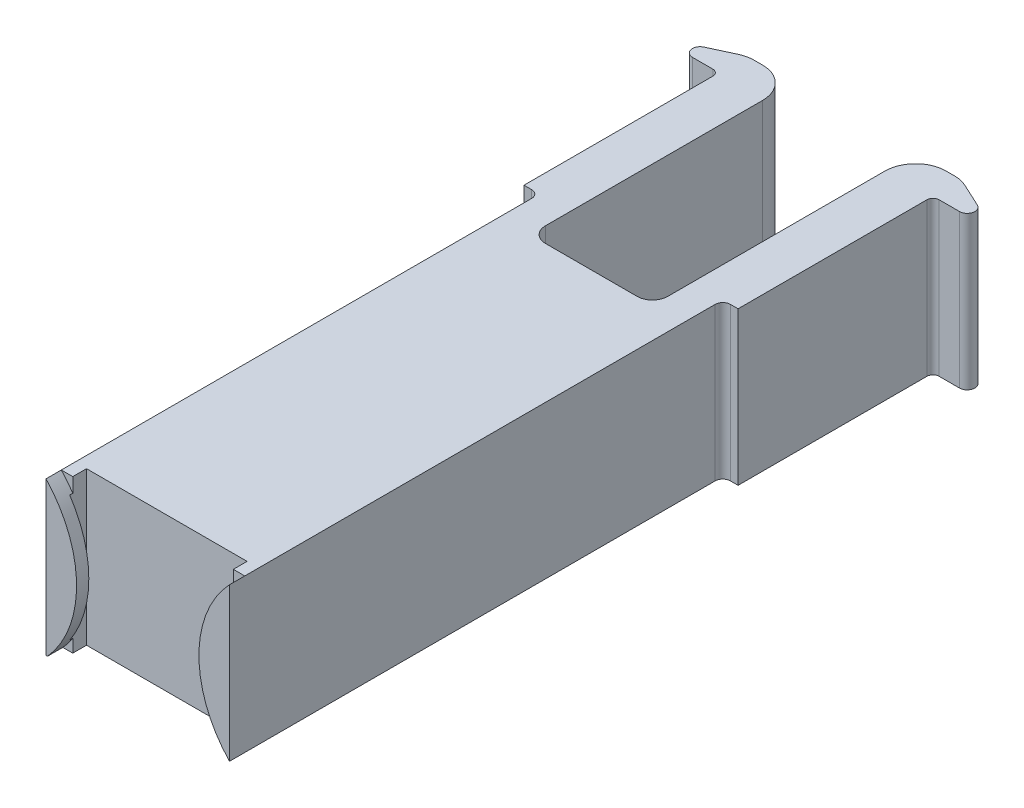
SolidWorks part; units mm, degrees
ref_plane "Front Plane" through (0, 0, 0) normal (0, 0, 1) x (1, 0, 0)
ref_plane "Top Plane" through (0, 0, 0) normal (0, 1, 0) x (1, 0, 0)
ref_plane "Right Plane" through (0, 0, 0) normal (1, 0, 0) x (0, 0, -1)
sketch "Sketch2" plane through (0, 0, 0) normal (0, 1, 0) x (1, 0, 0)
  line L3 (-3.4455, -4.1194) -> (3.5545, -4.1194)
  line L7 (-3.4455, 8.9823) -> (-1.9455, 8.9823)
  line L10 (3.5545, 8.9823) -> (2.0545, 8.9823)
  line L17 (-1.9455, 0.3806) -> (2.0545, 0.3806)
  line L19 (3.5545, 8.0548) -> (5.5545, 8.0548)
  line L20 (-3.4455, 8.0548) -> (-5.4455, 8.0548)
  line L21 (-3.4455, 8.9823) -> (-5.4455, 8.0548)
  line L22 (3.5545, 8.9823) -> (5.5545, 8.0548)
  line L23 (-3.4455, 8.0548) -> (-3.4455, -4.1194)
  line L24 (3.5545, 8.0548) -> (3.5545, -4.1194)
  line L25 (2.0545, 8.9823) -> (2.0545, 0.3806)
  line L26 (-1.9455, 8.9823) -> (-1.9455, 0.3806)
  point P0 (0, 0)
  dimension "D1" = 7
  dimension "D3" = 1.5
  dimension "D4" = 1.5
  dimension "D5" = 2
  dimension "D6" = 2
  dimension "D7" = 4.5
extrude "Boss-Extrude1" add sketch "Sketch2" along normal blind 5
fillet "Fillet2" radius 0.2 2 edges at (3.5545, 2.5, -8.0548) (-3.4455, 2.5, -8.0548)
fillet "Fillet3" radius 1 4 edges at (3.5545, 2.5, -8.9823) (-3.4455, 2.5, -8.9823) (-1.9455, 2.5, -8.9823) (2.0545, 2.5, -8.9823)
fillet "Fillet6" radius 0.5 2 edges at (2.0545, 2.5, -0.3806) (-1.9455, 2.5, -0.3806)
sketch "Sketch3" plane through (0, 0, 4.1194) normal (0, 0, 1) x (1, 0, 0)
  line L0 (-3.4455, 2.5) -> (3.5545, 2.5) construction
  line L18 (-3.4455, 5) -> (-3.4455, 0) construction
  line L23 (3.5545, 5) -> (3.5545, 0) construction
  line L24 (0.0545, 5) -> (0.0545, 0) construction
  line L25 (-3.4455, 5) -> (3.5545, 5) construction
  line L26 (-3.4455, 0) -> (3.5545, 0) construction
  line L28 (3.5545, 0) -> (-3.4455, 0)
  line L29 (3.5545, 0) -> (3.5545, 5)
  line L30 (3.5545, 5) -> (-3.4455, 5)
  line L31 (-3.4455, 0) -> (-3.4455, 5)
  line L32 (3.5545, 0) -> (-3.4455, 5) construction
  line L33 (3.5545, 5) -> (-3.4455, 0) construction
  point P4 (-0.4455, 2.5)
  point P5 (0.0545, 2.5)
  point P7 (0.0545, 2.5)
  point P13 (-0.4455, 2.5)
  point P16 (0.0545, 2.5)
extrude "Boss-Extrude2" add sketch "Sketch3" along normal blind 7.2
sketch "Sketch4" plane through (0, 0, 11.3194) normal (0, 0, 1) x (1, 0, 0)
  line L0 (0.0545, 5) -> (0.0545, 0) construction
  line L7 (3.5545, 5) -> (-3.4455, 5) construction
  line L16 (-3.4455, 0) -> (3.5545, 0) construction
  line L18 (-2.9455, 0) -> (3.0545, 0)
  line L19 (-2.9455, 0) -> (-2.9455, 5)
  line L20 (-2.9455, 5) -> (3.0545, 5)
  line L21 (3.0545, 0) -> (3.0545, 5)
  line L22 (-2.9455, 0) -> (3.0545, 5) construction
  line L23 (-2.9455, 5) -> (3.0545, 0) construction
  point P0 (-1.3283, 2)
  point P7 (0.0545, 3.125)
  point P8 (0.0545, 2.5)
  point P9 (0.0545, 2.5)
  dimension "D1" = 6
extrude "Boss-Extrude3" add sketch "Sketch4" along normal blind 3.13 contours L20 L21 L18 L19
sketch "Sketch5" plane through (0, 5, 0) normal (0, 1, 0) x (1, 0, 0)
  line L3 (-2.9455, -14.4494) -> (-2.9455, -14.0494) construction
  line L8 (-2.9455, -14.4494) -> (-2.9455, -11.3194) construction
  line L15 (-2.9455, -14.0494) -> (-2.5705, -14.0494) construction
  line L17 (-2.5705, -14.0494) -> (2.6795, -14.0494)
  line L18 (-2.5705, -14.0494) -> (-2.5705, -13.4994)
  line L19 (-2.5705, -13.4994) -> (2.6795, -13.4994)
  line L20 (2.6795, -14.0494) -> (2.6795, -13.4994)
  point P9 (0.0545, -19.4444)
  dimension "D1" = 0.4
  dimension "D2" = 0.375
  dimension "D3" = 5.25
  dimension "D4" = 0.55
extrude "Cut-Extrude1" cut sketch "Sketch5" against normal blind 6
fillet "Fillet8" radius 0.25 2 edges at (-5.4455, 2.5, -8.0548) (5.5545, 2.5, -8.0548)
sketch "Sketch9" plane through (0, 0, 11.3194) normal (0, 0, 1) x (1, 0, 0)
  line L9 (-2.9455, 5) -> (-3.5508, 5)
  line L10 (-2.9455, 5) -> (-2.9455, 0)
  line L11 (-2.9455, 0) -> (-3.5508, 0)
  line L12 (-3.5508, 5) -> (-3.5508, 0)
sketch "Sketch10" plane through (0, 0, 11.3194) normal (0, 0, 1) x (1, 0, 0)
  line L5 (3.0545, 5) -> (3.5545, 5)
  line L6 (3.0545, 5) -> (3.0545, 0)
  line L7 (3.0545, 0) -> (3.5545, 0)
  line L8 (3.5545, 5) -> (3.5545, 0)
extrude "Cut-Extrude5" cut sketch "Sketch9" against normal blind 13 contours L12 L11 L10 L9
extrude "Cut-Extrude6" cut sketch "Sketch10" against normal blind 13 contours L5 L8 L7 L6
fillet "Fillet16" radius 0.25 2 edges at (-2.9455, 2.5, -1.6806) (3.0545, 2.5, -1.6806)
sketch "Sketch12" plane through (0, 0, 14.4494) normal (0, 0, 1) x (1, 0, 0)
  line L0 (-2.9455, 5) -> (3.0545, 0) construction
  line L1 (-2.9455, 0) -> (3.0545, 0) construction
  line L2 (2.0545, 5) -> (-1.9455, 5)
  line L3 (2.0545, 5) -> (2.0545, 0)
  line L4 (2.0545, 0) -> (-1.9455, 0)
  line L5 (-1.9455, 5) -> (-1.9455, 0)
  line L6 (2.0545, 5) -> (-1.9455, 0) construction
  line L7 (2.0545, 0) -> (-1.9455, 5) construction
  point P2 (0.0545, 2.5)
  dimension "D1" = 4
extrude "Cut-Extrude7" cut sketch "Sketch12" against normal up to surface (0.4 mm away) up to face at (0.0545, 2.5, 14.0494)
sketch "Sketch14" plane through (0, 0, 14.4494) normal (0, 0, 1) x (1, 0, 0)
  line L0 (-2.9455, 0) -> (-1.9455, 0) construction
  line L2 (-2.9455, 5) -> (-1.9455, 5)
  line L3 (-2.9455, 5) -> (-2.9455, 0)
  line L4 (-2.9455, 0) -> (-1.9455, 0)
  line L5 (-1.9455, 5) -> (-1.9455, 0)
  line L6 (3.0545, 0) -> (2.0545, 0)
  line L7 (3.0545, 0) -> (3.0545, 5)
  line L8 (3.0545, 5) -> (2.0545, 5)
  line L9 (2.0545, 0) -> (2.0545, 5)
  arc A2 (-2.9455, 5) -> (-2.896, 0) centre (-5.6381, 2.4731) cw
  arc A3 (3.0545, 5) -> (3.0545, 0) centre (5.6795, 2.5) ccw
  line M3 (-1.9455, 0) -> (-1.9455, 5)
  line M4 (-1.9455, 5) -> (-2.9455, 5)
extrude "Cut-Extrude8" cut sketch "Sketch14" against normal blind 0.5 contours A2 L5 M4 | A2 L4 M3 | A3 L9 L6 | A3 L8 L9
